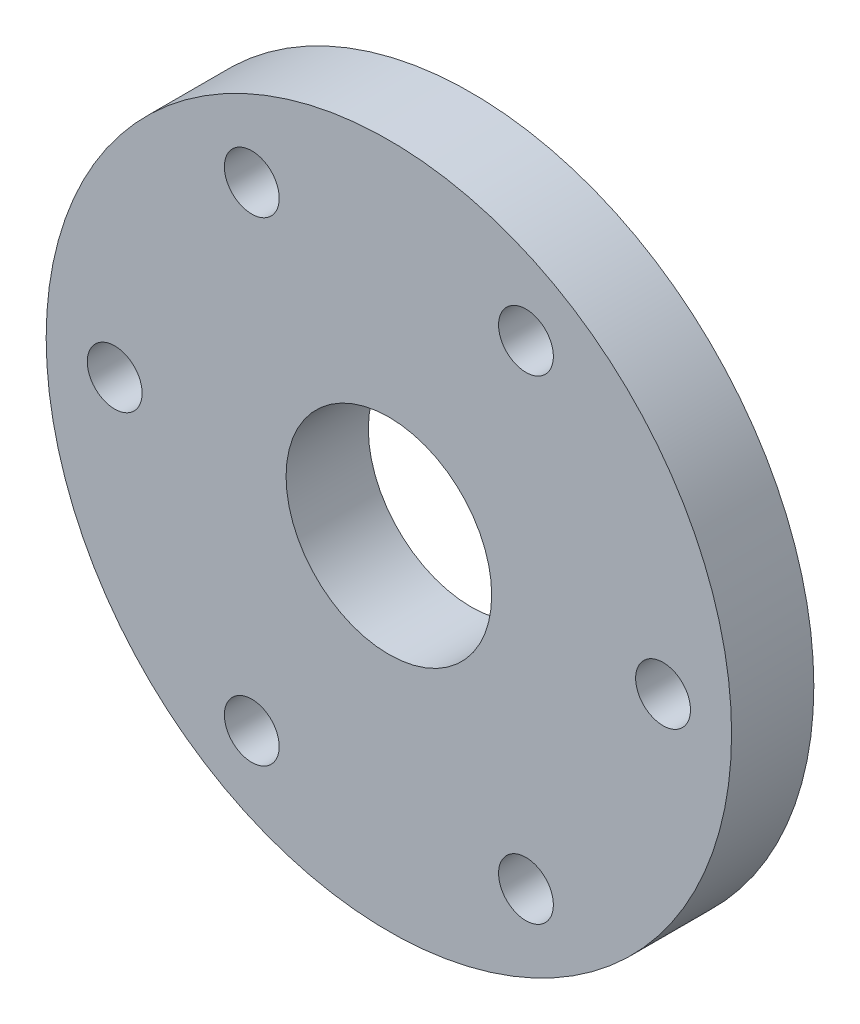
SolidWorks part; units mm, degrees
ref_plane "前视基准面" through (0, 0, 0) normal (0, 0, 1) x (1, 0, 0)
ref_plane "上视基准面" through (0, 0, 0) normal (0, 1, 0) x (1, 0, 0)
ref_plane "右视基准面" through (0, 0, 0) normal (1, 0, 0) x (0, 0, -1)
sketch "草图1" plane through (0, 0, 0) normal (0, 0, 1) x (1, 0, 0)
  circle A0 centre (0, 0) radius 50
  circle A1 centre (0, 0) radius 15
extrude "凸台-拉伸1" add sketch "草图1" along normal blind 12
sketch "草图2" plane through (0, 0, 0) normal (0, 0, 1) x (1, 0, 0)
  circle A0 centre (40, 0) radius 4
  circle A1 centre (20, 34.641) radius 4
  circle A2 centre (-20, 34.641) radius 4
  circle A3 centre (-40, 0) radius 4
  circle A4 centre (-20, -34.641) radius 4
  circle A5 centre (20, -34.641) radius 4
extrude "切除-拉伸1" cut sketch "草图2" along normal through all
